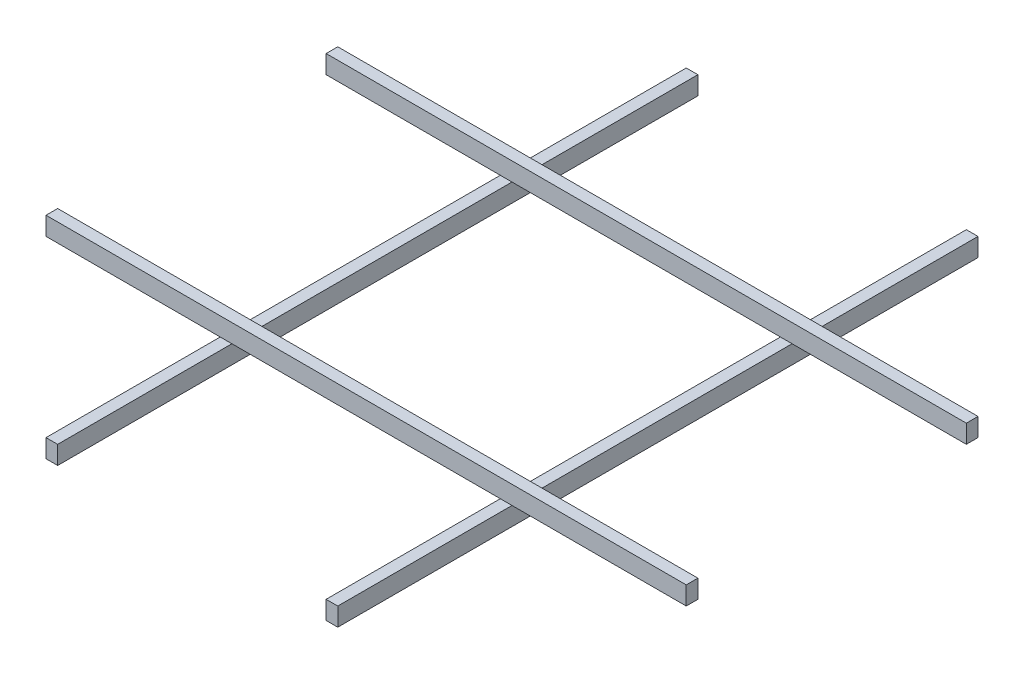
SolidWorks part; units mm, degrees
material "Doug Fir"
ref_plane "Front Plane" through (0, 0, 0) normal (0, 0, 1) x (1, 0, 0)
ref_plane "Top Plane" through (0, 0, 0) normal (0, 1, 0) x (1, 0, 0)
ref_plane "Right Plane" through (0, 0, 0) normal (1, 0, 0) x (0, 0, -1)
sketch "Lower Level" plane through (0, 0, 0) normal (0, 1, 0) x (1, 0, 0)
  line L0 (1066.8, 0) -> (1066.8, 4876.8)
  line L1 (3200.4, 0) -> (3200.4, 4876.8)
  line L2 (1066.8, 2438.4) -> (3200.4, 2438.4) construction
  point P7 (2133.6, 2438.4)
  dimension "D1" = 4876.8
  dimension "D2" = 1066.8
ref_plane "Plane2" through (0, 139.7, 0) normal (0, 1, 0) x (1, 0, 0)
sketch "Sketch12" plane through (0, 139.7, 0) normal (0, 1, 0) x (1, 0, 0)
  line L0 (-304.8, 3505.2) -> (4572, 3505.2)
  line L1 (4572, 1371.6) -> (-304.8, 1371.6)
  line L2 (2133.6, 3505.2) -> (2133.6, 1371.6) construction
  point P0 (2133.6, 2438.4)
  point P6 (2133.6, 1371.6)
  point P7 (2133.6, 3505.2)
  point P10 (2133.6, 2438.4)
  dimension "D1" = 4876.8
  dimension "D2" = 1066.8
other "Profiles 4X6(1)"
ref_plane "Plane1" through (1066.8, 0, 0) normal (0, 0, -1) x (-1, 0, 0)
sketch "Sketch1" plane through (1066.8, 0, 0) normal (0, 0, -1) x (-1, 0, 0)
  line L1 (-44.45, 69.85) -> (44.45, 69.85)
  line L2 (-44.45, 69.85) -> (-44.45, -69.85)
  line L3 (-44.45, -69.85) -> (44.45, -69.85)
  line L4 (44.45, 69.85) -> (44.45, -69.85)
  line L5 (-44.45, 69.85) -> (44.45, -69.85) construction
  line L6 (-44.45, -69.85) -> (44.45, 69.85) construction
  point P0 (0, 0)
  point P6 (0, 69.85)
  point P7 (0, -69.85)
  point P8 (44.45, 0)
  point P9 (-44.45, 0)
  point P10 (0, 0)
  dimension "D1" = 88.9
  dimension "D2" = 139.7
sketch3d "3DSketch2"
  line L0 (2133.6, 139.7, -2438.4) -> (2133.6, 0, -2438.4)
  line L1 (1066.8, 0, -2438.4) -> (3200.4, 0, -2438.4) construction
equation "\"Width\" = 42"
equation "\"Length\"=192"
equation "\"D1@Lower Level\"=\"Length\""
equation "\"D2@Lower Level\"=\"Width\""
equation "\"D1@Sketch12\"=\"Length\""
equation "\"D2@Sketch12\"=\"Width\""
